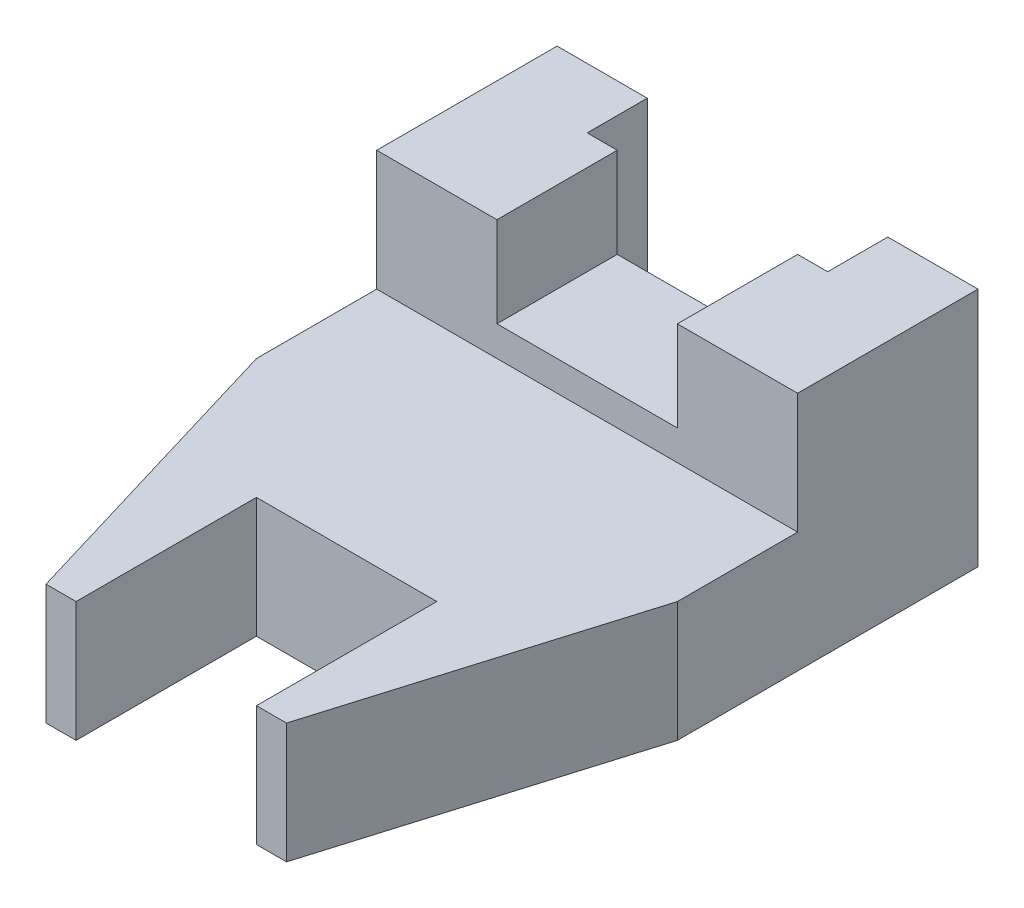
SolidWorks part; units mm, degrees
ref_plane "Front Plane" through (0, 0, 0) normal (0, 0, 1) x (1, 0, 0)
ref_plane "Top Plane" through (0, 0, 0) normal (0, 1, 0) x (1, 0, 0)
ref_plane "Right Plane" through (0, 0, 0) normal (1, 0, 0) x (0, 0, -1)
sketch "Sketch1" plane through (0, 0, 0) normal (0, 1, 0) x (1, 0, 0)
  line L2 (0, 0) -> (0, 50)
  line L3 (0, 50) -> (70, 50)
  line L4 (70, 0) -> (70, 50)
  line L7 (15, -50) -> (20, -50)
  line L9 (55, -50) -> (70, 0)
  line L10 (0, 0) -> (15, -50)
  line L11 (20, -50) -> (20, -20)
  line L12 (20, -20) -> (50, -20)
  line L13 (50, -20) -> (50, -50)
  line L14 (50, -50) -> (55, -50)
  dimension "D1" = 70
  dimension "D2" = 50
  dimension "D3" = 40
  dimension "D4" = 30
  dimension "D5" = 5
  dimension "D6" = 30
  dimension "D7" = 100
extrude "Boss-Extrude1" add sketch "Sketch1" along normal blind 20
sketch "Sketch2" plane through (0, 20, 0) normal (0, 1, 0) x (1, 0, 0)
  line L0 (0, 20) -> (70, 20)
  line L1 (0, 50) -> (0, 0) construction
  line L2 (70, 0) -> (70, 50) construction
  line L3 (70, 50) -> (0, 50) construction
  line L4 (0, 20) -> (0, 50)
  line L5 (0, 50) -> (70, 50)
  line L6 (70, 50) -> (70, 20)
  dimension "D1" = 30
extrude "Boss-Extrude2" add sketch "Sketch2" along normal blind 20
sketch "Sketch3" plane through (0, 40, 0) normal (0, 1, 0) x (1, 0, 0)
  line L0 (15, 40) -> (55, 40)
  line L1 (0, 50) -> (0, 20) construction
  line L2 (55, 40) -> (55, 50)
  line L3 (70, 50) -> (0, 50) construction
  line L4 (15, 40) -> (15, 50)
  line L5 (15, 50) -> (55, 50)
  dimension "D1" = 40
  dimension "D2" = 15
  dimension "D5" = 10
extrude "Cut-Extrude1" cut sketch "Sketch3" against normal up to next
sketch "Sketch4" plane through (0, 0, -20) normal (0, 0, 1) x (1, 0, 0)
  line L0 (20, 40) -> (20, 25)
  line L1 (0, 40) -> (70, 40) construction
  line L2 (20, 25) -> (50, 25)
  line L3 (50, 25) -> (50, 40)
  line L4 (70, 40) -> (70, 20) construction
  line L5 (20, 40) -> (50, 40)
  dimension "D1" = 30
  dimension "D2" = 20
  dimension "D3" = 15
extrude "Cut-Extrude2" cut sketch "Sketch4" against normal up to next
